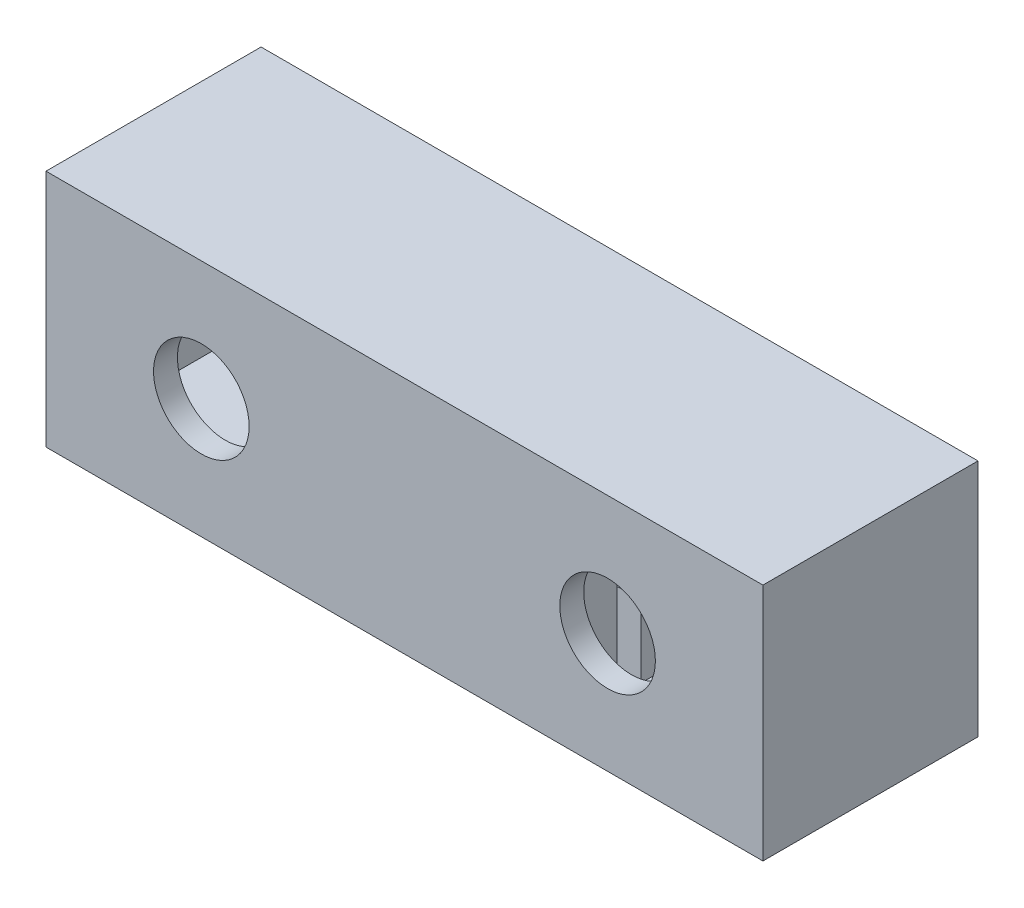
SolidWorks part; units mm, degrees
ref_plane "Front Plane" through (0, 0, 0) normal (0, 0, 1) x (1, 0, 0)
ref_plane "Top Plane" through (0, 0, 0) normal (0, 1, 0) x (1, 0, 0)
ref_plane "Right Plane" through (0, 0, 0) normal (1, 0, 0) x (0, 0, -1)
sketch "Sketch1" plane through (0, 0, 0) normal (0, 0, 1) x (1, 0, 0)
  line L0 (0, 122.1757) -> (0, -109.3517) construction
  line L1 (-171.4819, 0) -> (161.2493, 0) construction
  line L3 (-150, 50) -> (150, 50)
  line L4 (-150, 50) -> (-150, -50)
  line L5 (-150, -50) -> (150, -50)
  line L6 (150, 50) -> (150, -50)
  circle A0 centre (-85, 0) radius 20
  circle A1 centre (85, 0) radius 20
  point P11 (-150, 0)
  point P14 (150, 0)
  dimension "D5" = 65
  dimension "D6" = 65
  dimension "D1" = 150
  dimension "D2" = 150
  dimension "D3" = 100
  dimension "D4" = 50
extrude "Boss-Extrude1" add sketch "Sketch1" along normal blind 10
sketch "Sketch2" plane through (0, 0, 0) normal (0, 0, -1) x (-1, 0, 0)
  line L0 (0, 121.5619) -> (0, -123.072) construction
  line L1 (-185.2372, 0) -> (193.7943, 0) construction
  line L2 (-150, 50) -> (150, 50)
  line L3 (150, 50) -> (150, -50)
  line L4 (150, -50) -> (-150, -50)
  line L5 (-150, -50) -> (-150, 50)
  line L6 (-140, -40) -> (-140, 40)
  line L7 (-140, 40) -> (140, 40)
  line L8 (140, 40) -> (140, -40)
  line L9 (140, -40) -> (-140, -40)
  dimension "D1" = 10
extrude "Boss-Extrude2" add sketch "Sketch2" along normal blind 50
sketch "Sketch3" plane through (0, 0, 0) normal (0, 0, -1) x (-1, 0, 0)
  line L0 (-186.2439, 0) -> (181.2103, 0) construction
  line L1 (0, 110.9913) -> (0, -116.5283) construction
  line L2 (-60, 10) -> (-60, 40)
  line L3 (-60, 10) -> (60, 10)
  line L5 (-60, -10) -> (60, -10)
  line L7 (140, 40) -> (-140, 40) construction
  line L8 (-60, 40) -> (60, 40)
  line L9 (60, 40) -> (60, 10)
  line L10 (60, -40) -> (-60, -40)
  line L11 (-140, -40) -> (140, -40) construction
  line L12 (-60, -40) -> (-60, -10)
  line L13 (60, -10) -> (60, -40)
  dimension "D1" = 20
  dimension "D2" = 10
extrude "Boss-Extrude3" add sketch "Sketch3" along normal blind 50
sketch "Sketch4" plane through (0, 0, 0) normal (0, 0, -1) x (-1, 0, 0)
  line L0 (-60, -10) -> (-60, 10)
  line L1 (-60, 10) -> (60, 10)
  line L2 (60, 10) -> (60, -10)
  line L3 (60, -10) -> (-60, -10)
extrude "Boss-Extrude4" add sketch "Sketch4" along normal blind 19
sketch "Sketch7" plane through (60, 0, 0) normal (1, 0, 0) x (0, 0, -1)
  line L0 (19, 10) -> (19, 40)
  line L1 (50, 40) -> (0, 40) construction
  line L2 (19, 40) -> (50, 40)
  line L3 (50, 40) -> (50, 10)
  line L4 (50, 40) -> (50, 10) construction
  line L5 (50, 10) -> (19, 10) construction
  line L6 (50, 10) -> (19, 10)
  line L7 (19, -10) -> (50, -10)
  line L8 (50, -10) -> (50, -40)
  line L9 (50, -40) -> (19, -40)
  line L10 (50, -40) -> (0, -40) construction
  line L11 (19, -40) -> (19, -10)
extrude "Boss-Extrude5" add sketch "Sketch7" along normal blind 10
sketch "Sketch8" plane through (-60, 0, 0) normal (-1, 0, 0) x (0, 0, 1)
  line L0 (-50, 40) -> (-50, 10)
  line L1 (-50, 10) -> (-19, 10)
  line L2 (-19, 10) -> (-19, 40)
  line L3 (-50, 40) -> (0, 40) construction
  line L4 (-19, 40) -> (-50, 40)
  line L5 (-50, -10) -> (-19, -10)
  line L6 (-19, -10) -> (-19, -40)
  line L7 (-50, -40) -> (0, -40) construction
  line L8 (-19, -40) -> (-50, -40)
  line L9 (-50, -40) -> (-50, -10)
extrude "Boss-Extrude6" add sketch "Sketch8" along normal blind 10
sketch "Sketch9" plane through (0, 0, -50) normal (0, 0, -1) x (-1, 0, 0)
  line L0 (-150, 50) -> (150, 50)
  line L1 (150, 50) -> (150, -50)
  line L2 (150, -50) -> (-150, -50)
  line L3 (-150, -50) -> (-150, 50)
  line L4 (-140, -40) -> (-140, 40)
  line L5 (-140, 40) -> (140, 40)
  line L6 (140, 40) -> (140, -40)
  line L7 (140, -40) -> (-140, -40)
  dimension "D1" = 10
extrude "Boss-Extrude7" add sketch "Sketch9" along normal blind 30
